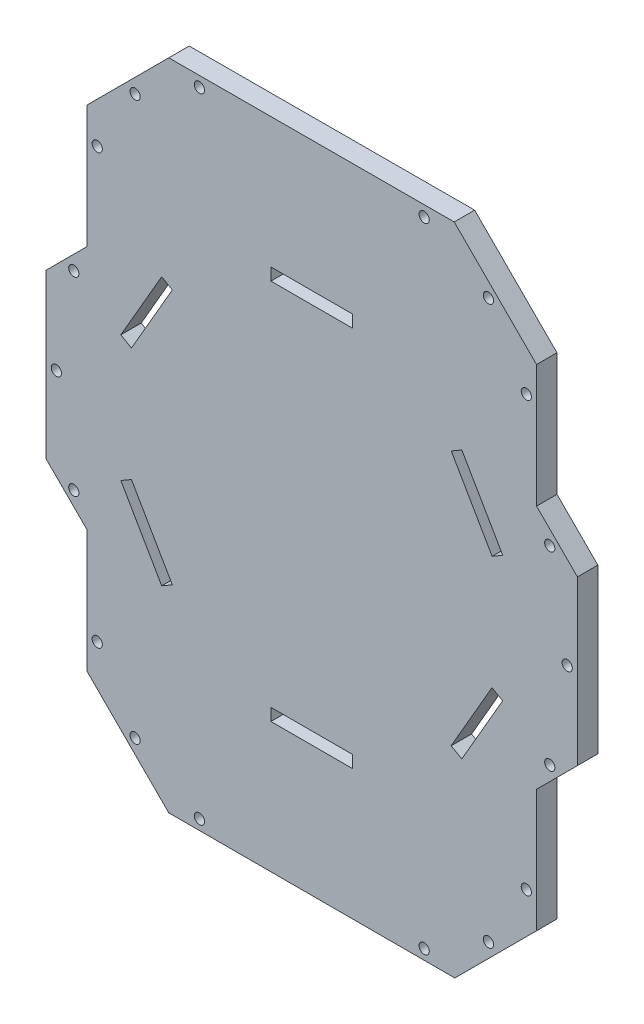
SolidWorks part; units mm, degrees
ref_plane "Front Plane" through (0, 0, 0) normal (0, 0, 1) x (1, 0, 0)
ref_plane "Top Plane" through (0, 0, 0) normal (0, 1, 0) x (1, 0, 0)
ref_plane "Right Plane" through (0, 0, 0) normal (1, 0, 0) x (0, 0, -1)
sketch "Model" plane through (0, 0, 0) normal (0, 0, 1) x (1, 0, 0)
  line L0 (67.4438, 135.7464) -> (67.4438, 132.7464)
  line L1 (67.4438, 132.7464) -> (87.4438, 132.7464)
  line L2 (87.4438, 132.7464) -> (87.4438, 135.7464)
  line L3 (87.4438, 135.7464) -> (67.4438, 135.7464)
  line L4 (67.4438, 42.4239) -> (67.4438, 39.4239)
  line L5 (67.4438, 39.4239) -> (87.4438, 39.4239)
  line L6 (87.4438, 39.4239) -> (87.4438, 42.4239)
  line L7 (87.4438, 42.4239) -> (67.4438, 42.4239)
  line L8 (111.5461, 56.3296) -> (114.1441, 54.8296)
  line L9 (114.1441, 54.8296) -> (124.1441, 72.1501)
  line L10 (124.1441, 72.1501) -> (121.5461, 73.6501)
  line L11 (121.5461, 73.6501) -> (111.5461, 56.3296)
  line L12 (114.1696, 120.3163) -> (111.5715, 118.8163)
  line L13 (111.5715, 118.8163) -> (121.5715, 101.4957)
  line L14 (121.5715, 101.4957) -> (124.1696, 102.9957)
  line L15 (124.1696, 102.9957) -> (114.1696, 120.3163)
  line L16 (40.718, 54.8149) -> (43.316, 56.3149)
  line L17 (43.316, 56.3149) -> (33.316, 73.6354)
  line L18 (33.316, 73.6354) -> (30.718, 72.1354)
  line L19 (30.718, 72.1354) -> (40.718, 54.8149)
  line L20 (30.718, 102.9957) -> (33.316, 101.4957)
  line L21 (33.316, 101.4957) -> (43.316, 118.8163)
  line L22 (43.316, 118.8163) -> (40.718, 120.3163)
  line L23 (40.718, 120.3163) -> (30.718, 102.9957)
  line L24 (112.4438, 7.5656) -> (132.4438, 27.5656)
  line L25 (112.2985, 167.7108) -> (132.4438, 147.5656)
  line L26 (42.4438, 7.5656) -> (22.4438, 27.5656)
  line L27 (12.4438, 67.5656) -> (12.4438, 107.5656)
  line L28 (42.4475, 167.5694) -> (22.4438, 147.5656)
  line L29 (22.4438, 27.5656) -> (22.4438, 57.5656)
  line L30 (12.4438, 67.5656) -> (22.4438, 57.5656)
  line L31 (22.4438, 147.5656) -> (22.4438, 117.5656)
  line L32 (12.4438, 107.5656) -> (22.4438, 117.5656)
  line L33 (142.4438, 67.5656) -> (142.4438, 107.5656)
  line L34 (132.4438, 27.5656) -> (132.4438, 57.5656)
  line L35 (142.4438, 67.5656) -> (132.4438, 57.5656)
  line L36 (132.4438, 147.5656) -> (132.4438, 117.5656)
  line L37 (142.4438, 107.5656) -> (132.4438, 117.5656)
  line L38 (42.4438, 7.5656) -> (112.4438, 7.5656)
  line L39 (42.4475, 167.5694) -> (112.2985, 167.7108)
  circle A0 centre (104.9438, 10.0656) radius 1.25
  circle A1 centre (129.9438, 35.0656) radius 1.25
  circle A2 centre (120.676, 19.3334) radius 1.25
  circle A3 centre (49.9438, 10.0656) radius 1.25
  circle A4 centre (24.9438, 35.0656) radius 1.25
  circle A5 centre (34.2115, 19.3334) radius 1.25
  circle A6 centre (104.9438, 165.0656) radius 1.25
  circle A7 centre (129.9438, 140.0656) radius 1.25
  circle A8 centre (120.676, 155.7978) radius 1.25
  circle A9 centre (49.9438, 165.0656) radius 1.25
  circle A10 centre (24.9438, 140.0656) radius 1.25
  circle A11 centre (34.2115, 155.7978) radius 1.25
  circle A12 centre (19.2115, 64.3334) radius 1.25
  circle A13 centre (14.9438, 87.5656) radius 1.25
  circle A14 centre (19.2115, 110.7978) radius 1.25
  circle A15 centre (135.676, 64.3334) radius 1.25
  circle A16 centre (139.9438, 87.5656) radius 1.25
  circle A17 centre (135.676, 110.7978) radius 1.25
extrude "Boss-Extrude1" add sketch "Model" along normal blind 5
